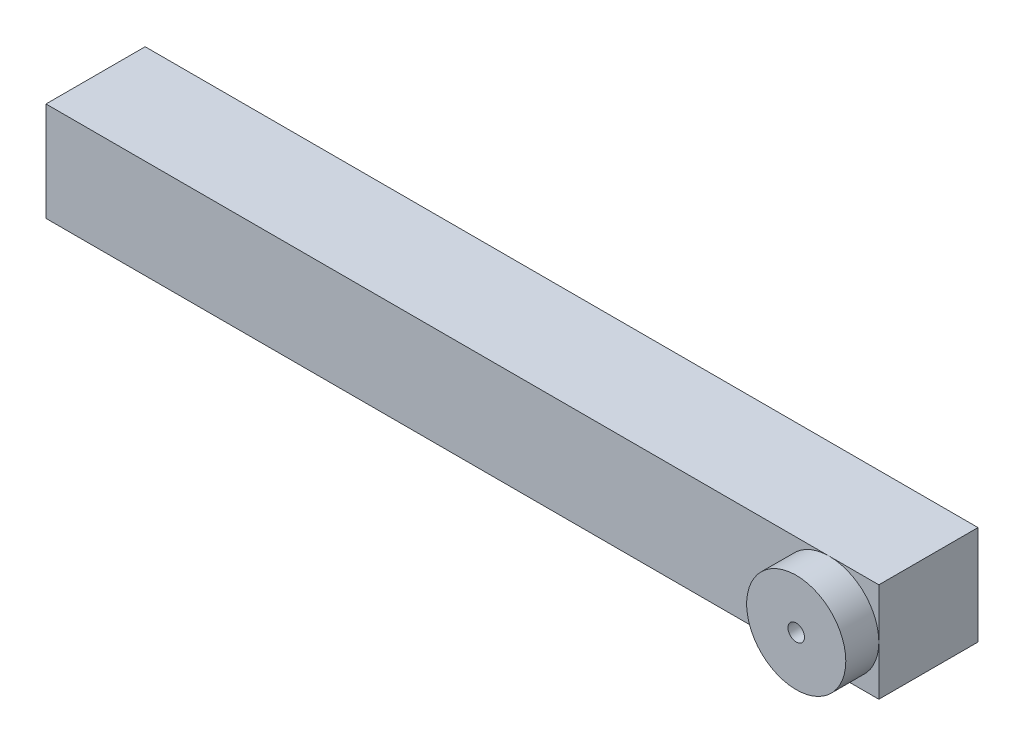
SolidWorks part; units mm, degrees
ref_plane "Front Plane" through (0, 0, 0) normal (0, 0, 1) x (1, 0, 0)
ref_plane "Top Plane" through (0, 0, 0) normal (0, 1, 0) x (1, 0, 0)
ref_plane "Right Plane" through (0, 0, 0) normal (1, 0, 0) x (0, 0, -1)
sketch "Sketch2" plane through (0, 0, 0) normal (1, 0, 0) x (0, 0, -1)
  line L1 (0, 0) -> (30, 0)
  line L2 (0, 0) -> (0, 30)
  line L3 (0, 30) -> (30, 30)
  line L4 (30, 0) -> (30, 30)
  dimension "D1" = 30
  dimension "D2" = 30
extrude "Boss-Extrude1" add sketch "Sketch2" along normal blind 252
sketch "Sketch3" plane through (0, 0, 0) normal (0, 0, 1) x (1, 0, 0)
  line L0 (252, 30) -> (0, 30) construction
  line L1 (252, 30) -> (252, 0) construction
  circle A0 centre (237, 15) radius 15
  dimension "D1" = 30
  dimension "D2" = 15
  dimension "D3" = 15
extrude "Boss-Extrude2" add sketch "Sketch3" along normal blind 10
sketch "Sketch4" plane through (0, 0, 10) normal (0, 0, 1) x (1, 0, 0)
  line L0 (252, 30) -> (252, 15) construction
  circle A0 centre (237, 15) radius 2.5
  point P5 (252.695, 24.1852)
  dimension "D1" = 15
  dimension "D3" = 5
  dimension "D2" = 15
extrude "Cut-Extrude1" cut sketch "Sketch4" against normal blind 4
